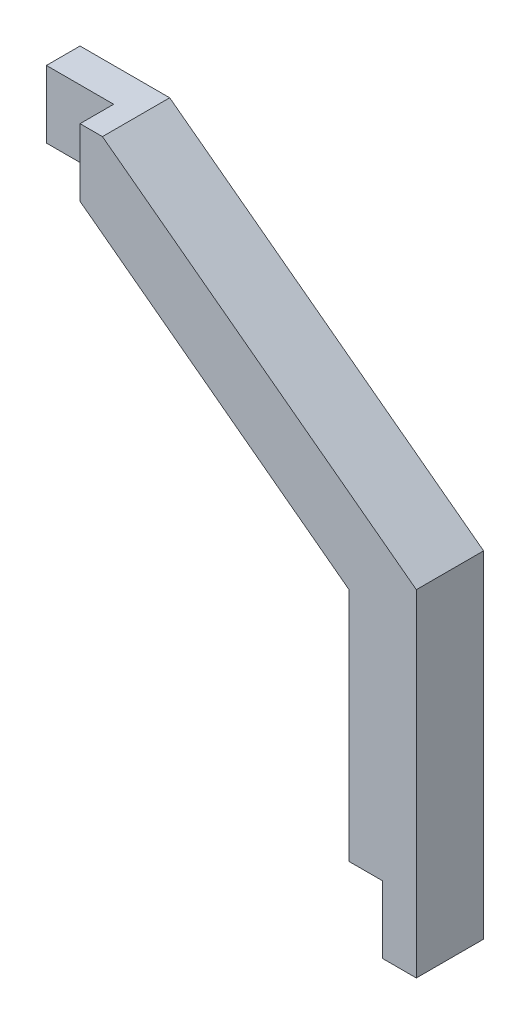
SolidWorks part; units mm, degrees
ref_plane "Alzado" through (0, 0, 0) normal (0, 0, 1) x (1, 0, 0)
ref_plane "Planta" through (0, 0, 0) normal (0, 1, 0) x (1, 0, 0)
ref_plane "Vista lateral" through (0, 0, 0) normal (1, 0, 0) x (0, 0, -1)
sketch "Croquis1" plane through (0, 0, 0) normal (0, 0, 1) x (1, 0, 0)
  line L0 (-60, 0) -> (60, 0) construction
  line L1 (-60, 0) -> (-33.3333, 0)
  line L2 (-33.3333, 0) -> (60, -70)
  line L3 (60, -70) -> (60, -170)
  line L4 (60, -170) -> (40, -170)
  line L5 (40, -170) -> (40, -80)
  line L6 (40, -80) -> (-40, -20)
  line L7 (-40, -20) -> (-60, -20)
  line L8 (-60, -20) -> (-60, 0)
  line L9 (60, -170) -> (60, -160) construction
  point P0 (-60, -10)
  point P4 (0, 0)
  dimension "D1" = 150
  dimension "D2" = 120
  dimension "D3" = 20
  dimension "D4" = 20
  dimension "D5" = 20
  dimension "D6" = 90
  dimension "D7" = 20
  dimension "D8" = 10
extrude "Saliente-Extruir1" add sketch "Croquis1" along normal blind 20 contours L1 L2 L3 L4 L5 L6 L7 L8
sketch "Croquis2" plane through (0, 0, 20) normal (0, 0, 1) x (1, 0, 0)
  line L0 (-60, -20) -> (-40, -20)
  line L1 (-40, -20) -> (-40, 0)
  line L2 (-60, 0) -> (-33.3333, 0) construction
  line L3 (-40, 0) -> (-60, 0)
  line L4 (-60, 0) -> (-60, -20)
extrude "Cortar-Extruir1" cut sketch "Croquis2" against normal blind 10
sketch "Croquis3" plane through (40, 0, 0) normal (1, 0, 0) x (0, 0, -1)
  line L0 (-20, -170) -> (0, -170)
  line L1 (0, -170) -> (0, -150)
  line L2 (0, -70) -> (0, -170) construction
  line L3 (0, -150) -> (-20, -150)
  line L4 (-20, -70) -> (-20, -170) construction
  line L5 (-20, -150) -> (-20, -170)
  dimension "D1" = 20
extrude "Cortar-Extruir2" cut sketch "Croquis3" along normal blind 10
